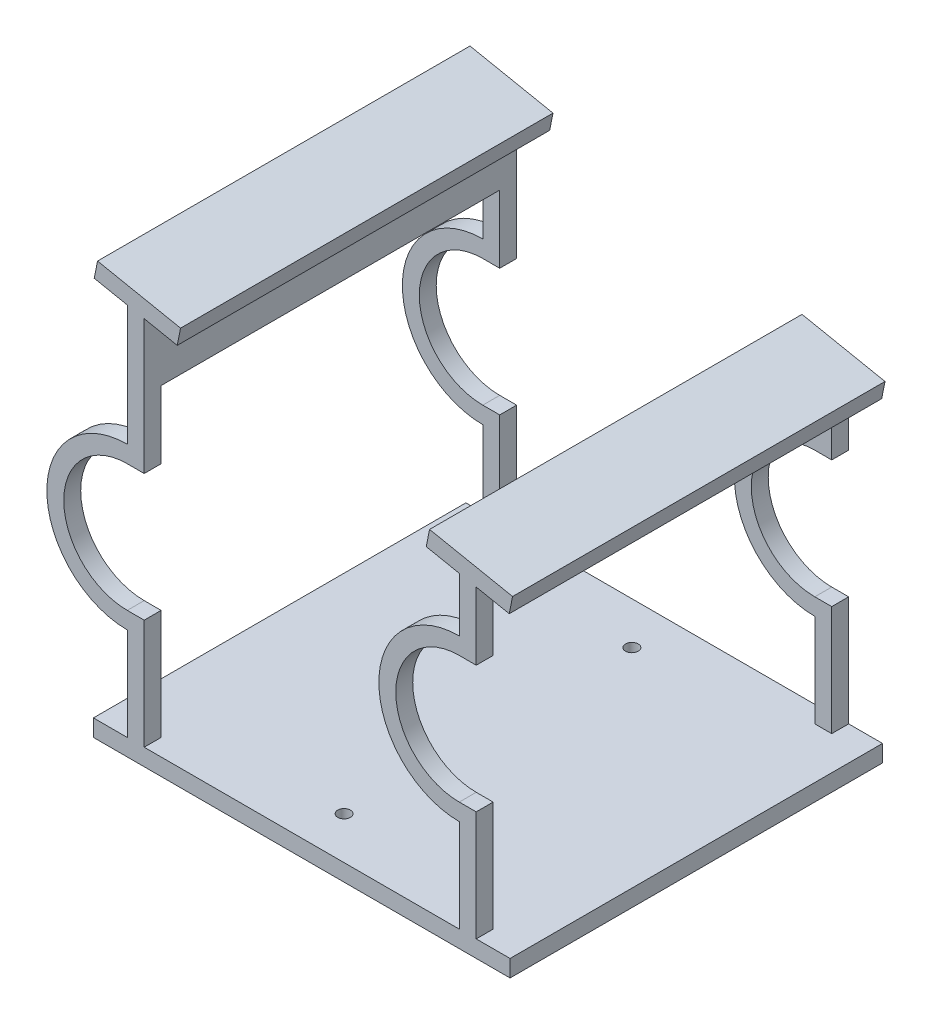
SolidWorks part; units mm, degrees
ref_plane "Front Plane" through (0, 0, 0) normal (0, 0, 1) x (1, 0, 0)
ref_plane "Top Plane" through (0, 0, 0) normal (0, 1, 0) x (1, 0, 0)
ref_plane "Right Plane" through (0, 0, 0) normal (1, 0, 0) x (0, 0, -1)
sketch "Sketch1" plane through (0, 0, 0) normal (0, 0, 1) x (1, 0, 0)
  line L0 (100, -20) -> (0, 0) construction
  line L1 (100, -20) -> (0, 0) construction
  line L2 (25.4855, -5.0971) -> (25.0933, -7.0583)
  line L4 (34.8991, -9.0194) -> (35.2913, -7.0583)
  line L5 (35.2913, -7.0583) -> (25.4855, -5.0971)
  line L6 (64.7087, -12.9417) -> (64.3165, -14.9029)
  line L8 (74.1223, -16.8641) -> (74.5145, -14.9029)
  line L9 (74.5145, -14.9029) -> (64.7087, -12.9417)
  line L10 (50, -10) -> (34.8991, -9.0194) construction
  line L11 (50, -10) -> (64.3165, -14.9029) construction
  line L12 (28.9962, -7.8388) -> (28.9962, -22.0835)
  line L13 (30.9962, -8.2388) -> (30.9962, -24.0835)
  line L18 (68.2194, -15.6835) -> (68.2194, -22.0835)
  line L19 (70.2194, -16.0835) -> (70.2194, -20.0835)
  line L21 (64.3165, -14.9029) -> (68.2194, -15.6835)
  line L22 (70.2194, -16.0835) -> (74.1223, -16.8641)
  line L23 (70.2194, -20.0835) -> (68.2194, -20.0835) construction
  line L24 (25.0933, -7.0583) -> (28.9962, -7.8388)
  line L25 (30.9962, -8.2388) -> (34.8991, -9.0194)
  line L26 (28.9962, -22.0835) -> (28.9962, -24.0835) construction
  line L27 (28.9962, -24.0835) -> (30.9962, -24.0835)
  line L28 (28.9962, -41.0835) -> (28.9962, -39.0835) construction
  line L29 (28.9962, -39.0835) -> (28.9962, -24.0835) construction
  line L30 (68.2194, -20.0835) -> (30.9962, -20.0835) construction
  line L31 (70.2194, -20.0835) -> (70.2194, -24.0835)
  line L32 (30.9962, -20.0835) -> (28.9962, -20.0835) construction
  line L33 (68.2194, -22.0835) -> (68.2194, -24.0835) construction
  line L34 (68.2194, -24.0835) -> (70.2194, -24.0835)
  line L35 (68.2194, -41.0835) -> (68.2194, -39.0835) construction
  line L36 (68.2194, -39.0835) -> (68.2194, -24.0835) construction
  line L37 (28.9962, -22.0835) -> (68.2194, -22.0835) construction
  line L38 (28.9962, -39.0835) -> (30.9962, -39.0835)
  line L40 (68.2194, -39.0835) -> (70.2194, -39.0835)
  line L41 (70.2194, -39.0835) -> (70.2194, -52.0835)
  line L42 (28.9962, -41.0835) -> (28.9962, -52.0835)
  line L44 (24.9962, -52.0835) -> (24.9962, -54.0835)
  line L50 (74.2194, -52.0835) -> (74.2194, -54.0835)
  line L51 (30.9962, -39.0835) -> (30.9962, -52.0835)
  line L52 (24.9962, -52.0835) -> (28.9962, -52.0835)
  line L53 (30.9962, -52.0835) -> (68.2194, -52.0835)
  line L54 (68.2194, -41.0835) -> (68.2194, -52.0835)
  line L56 (70.2194, -52.0835) -> (74.2194, -52.0835)
  line L57 (24.9962, -54.0835) -> (74.2194, -54.0835)
  arc A0 (28.9962, -22.0835) -> (28.9962, -41.0835) centre (28.9962, -31.5835) ccw
  arc A1 (28.9962, -24.0835) -> (28.9962, -39.0835) centre (28.9962, -31.5835) ccw
  arc A2 (68.2194, -22.0835) -> (68.2194, -41.0835) centre (68.2194, -31.5835) ccw
  arc A3 (68.2194, -24.0835) -> (68.2194, -39.0835) centre (68.2194, -31.5835) ccw
  point P28 (70.2194, -45.5835)
  dimension "D1" = 2
  dimension "D2" = 10
  dimension "D3" = 10
  dimension "D4" = 2
  dimension "D5" = 30
  dimension "D9" = 2
  dimension "D8" = 4
  dimension "D6" = 2
  dimension "D10" = 15
  dimension "D12" = 15
  dimension "D11" = 2
  dimension "D7" = 2
  dimension "D13" = 2
  dimension "D18" = 2
  dimension "D19" = 2
  dimension "D14" = 4
  dimension "D15" = 2
  dimension "D16" = 30
extrude "Boss-Extrude1" add sketch "Sketch1" against normal blind 44
sketch "Sketch2" plane through (70.2194, 0, 0) normal (1, 0, 0) x (0, 0, -1)
  line L0 (44, -16.0835) -> (0, -16.0835) construction
  line L1 (2, -16.0835) -> (42, -16.0835)
  line L2 (2, -16.0835) -> (2, -52.0835)
  line L3 (2, -52.0835) -> (42, -52.0835)
  line L4 (42, -16.0835) -> (42, -52.0835)
  line L5 (44, -52.0835) -> (0, -52.0835) construction
  line L6 (0, -24.0835) -> (0, -16.0835) construction
  line L7 (44, -24.0835) -> (44, -16.0835) construction
  dimension "D1" = 2
  dimension "D2" = 2
extrude "Cut-Extrude1" cut sketch "Sketch2" against normal through all
sketch "Sketch3" plane through (0, -52.0835, 0) normal (0, 1, 0) x (1, 0, 0)
  line L0 (49.6078, 0) -> (49.6078, 5) construction
  line L1 (68.2194, 0) -> (30.9962, 0) construction
  line L2 (49.6078, 44) -> (49.6078, 39) construction
  line L3 (68.2194, 44) -> (30.9962, 44) construction
  circle A0 centre (49.6078, 39) radius 0.75
  circle A1 centre (49.6078, 5) radius 0.75
  dimension "D2" = 1.5
  dimension "D1" = 5
extrude "Cut-Extrude2" cut sketch "Sketch3" against normal through all
equation "\"SlideVibrationCouplerHeight\"=30"
equation "\"D16@Sketch1\"=\"SlideVibrationCouplerHeight\""
